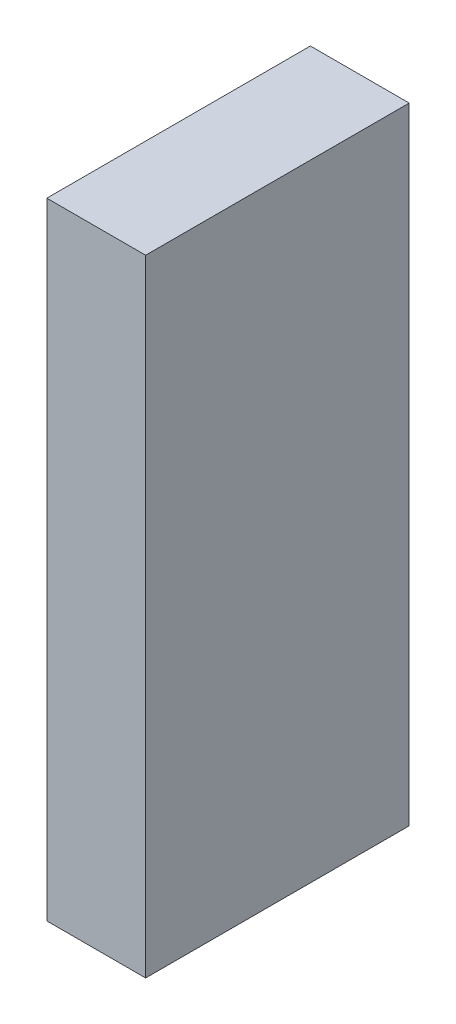
SolidWorks part; units mm, degrees
ref_plane "Front Plane" through (0, 0, 0) normal (0, 0, 1) x (1, 0, 0)
ref_plane "Top Plane" through (0, 0, 0) normal (0, 1, 0) x (1, 0, 0)
ref_plane "Right Plane" through (0, 0, 0) normal (1, 0, 0) x (0, 0, -1)
sketch "Sketch1" plane through (0, 0, 0) normal (1, 0, 0) x (0, 0, -1)
  line L1 (-20.129, 28.2581) -> (19.871, 28.2581)
  line L2 (-20.129, 28.2581) -> (-20.129, -66.7419)
  line L3 (-20.129, -66.7419) -> (19.871, -66.7419)
  line L4 (19.871, 28.2581) -> (19.871, -66.7419)
  dimension "D1" = 40
  dimension "D2" = 95
extrude "Boss-Extrude1" add sketch "Sketch1" along normal blind 15
